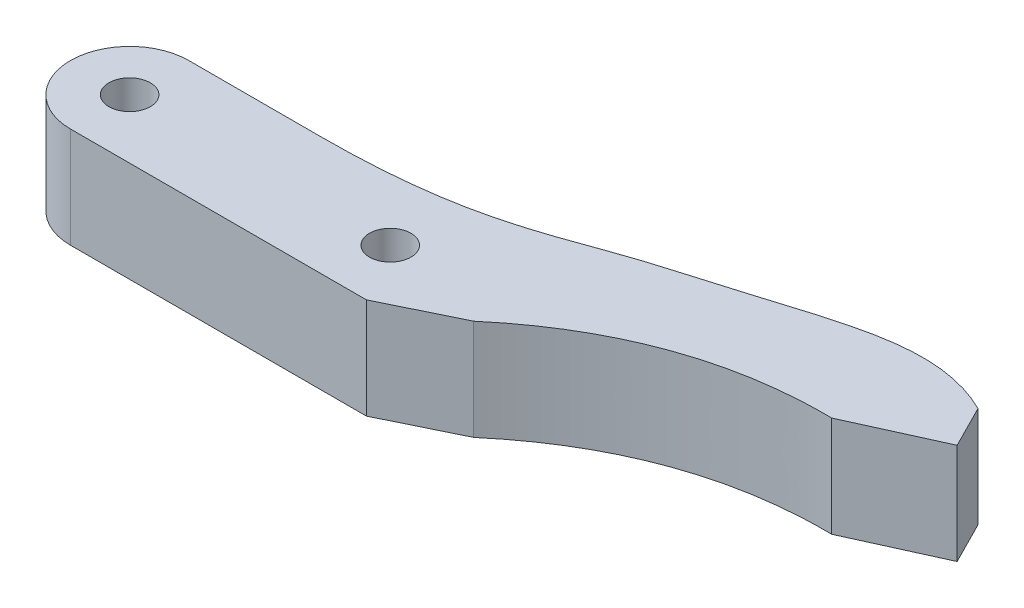
SolidWorks part; units mm, degrees
ref_plane "Front Plane" through (0, 0, 0) normal (0, 0, 1) x (1, 0, 0)
ref_plane "Top Plane" through (0, 0, 0) normal (0, 1, 0) x (1, 0, 0)
ref_plane "Right Plane" through (0, 0, 0) normal (1, 0, 0) x (0, 0, -1)
sketch "Sketch2" plane through (0, 0, 0) normal (0, 1, 0) x (1, 0, 0)
  line L1 (27, 5) -> (-5, 5)
  line L2 (27, 5) -> (27, -5)
  line L3 (27, -5) -> (-5, -5)
  line L4 (-5, 5) -> (-5, -5)
  line L5 (27, 5) -> (-5, -5) construction
  line L6 (27, -5) -> (-5, 5) construction
  circle A0 centre (0, 0) radius 1.75
  circle A1 centre (0, 0) radius 5
  circle A2 centre (22, 0) radius 1.75
  circle A3 centre (22, 0) radius 5
  point P7 (11, 0)
  dimension "D1" = 22
  dimension "D2" = 10
  dimension "D3" = 3.5
extrude "Boss-Extrude1" add sketch "Sketch2" along normal blind 8.5 contours A3 L1 A1 L3 | A1 A0 | A3 A2
sketch "Sketch3" plane through (0, 8.5, 0) normal (0, 1, 0) x (1, 0, 0)
  line L0 (22, -5) -> (24.99, -5)
  line L1 (22, -5) -> (0, -5) construction
  line L2 (24.99, -5) -> (31.08, -2.0297)
  line L3 (22, 5) -> (0, 5) construction
  line L4 (58.75, 12.87) -> (60.557, 9.3014)
  line L5 (60.557, 9.3014) -> (53.27, 6)
  line L6 (17.4898, 5) -> (4.4855, 5) construction
  line L7 (22, 5) -> (11, 5)
  circle A0 centre (22, 0) radius 1.75 construction
  arc A1 (22, -5) -> (22, 5) centre (22, 0) ccw construction
  arc A2 (22, -5) -> (22, 5) centre (22, 0) ccw
  spline S0 degree 3 poles (11, 5) (23.321, 5) (28.9604, 8.22) (46.0602, 12.9767) (52.5333, 15.9183) (58.75, 12.87) knots 0 0 0 0 0.362025 0.462025 1 1 1 1
  spline S1 degree 2 poles (31.08, -2.0297) (40.7387, 6.1883) (53.27, 6) knots 0 0 0 1 1 1
  dimension "D6" = 36.75
  dimension "D2" = 26
  dimension "D3" = 8
  dimension "D4" = 4
  dimension "D5" = 11
  dimension "D7" = 2.99
  dimension "D8" = 9.08
  dimension "D9" = 13.52
  dimension "D10" = 20.52
  dimension "D11" = 31.27
  dimension "D12" = 9.45
  dimension "D13" = 47.75
  dimension "D14" = 15.03
extrude "Boss-Extrude2" add sketch "Sketch3" against normal blind 8.5
sketch "Sketch4" plane through (0, 8.5, 0) normal (0, 1, 0) x (1, 0, 0)
  line L0 (0, 0) -> (57.5872, 0)
  line L1 (60.557, 9.3014) -> (40.0266, 0)
  dimension "D1" = 24.373
